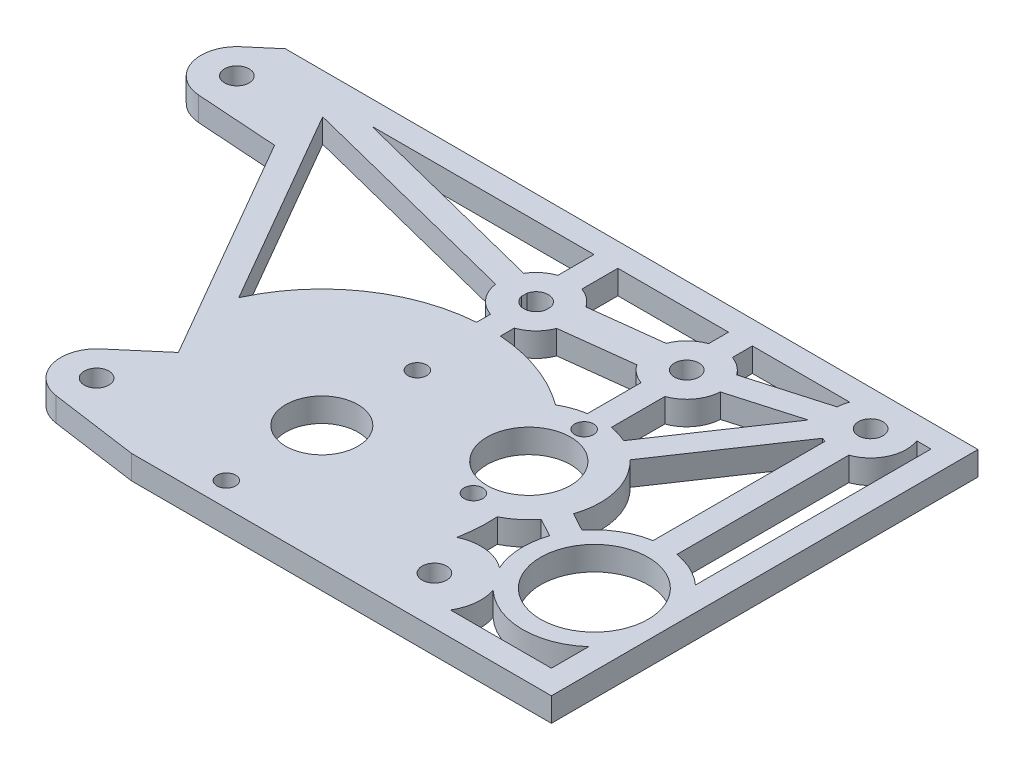
SolidWorks part; units mm, degrees
ref_plane "Front Plane" through (0, 0, 0) normal (0, 0, 1) x (1, 0, 0)
ref_plane "Top Plane" through (0, 0, 0) normal (0, 1, 0) x (1, 0, 0)
ref_plane "Right Plane" through (0, 0, 0) normal (1, 0, 0) x (0, 0, -1)
sketch "Sketch1" plane through (0, 0, 0) normal (0, 1, 0) x (1, 0, 0)
  line L0 (-155.0877, 84.2963) -> (-89.4632, -29.3687)
  line L1 (-89.4632, -29.3687) -> (152.4261, -29.3687)
  line L2 (152.4261, -29.3687) -> (218.0506, 84.2963)
  line L3 (218.0506, 84.2963) -> (-155.0877, 84.2963)
  line L4 (-5.496, 21.6549) -> (-41.275, 2.3813) construction
  line L5 (-5.496, 21.6549) -> (32.4838, 1.1113) construction
  line L6 (61.7749, 67.4068) -> (117.3646, 77.9462) construction
  line L7 (117.3646, 77.9462) -> (98.6972, 24.5341) construction
  line L8 (98.6972, 24.5341) -> (107.7129, -23.0187) construction
  line L9 (61.7749, 67.4068) -> (98.6972, 24.5341) construction
  line L10 (45.9981, 77.1526) -> (118.9398, 90.9819)
  line L11 (45.9981, 77.1526) -> (58.5464, 30.5539)
  line L12 (-140.423, 84.2963) -> (-74.7985, -29.3687) construction
  line L13 (-125.7583, 84.2963) -> (-60.1338, -29.3687) construction
  line L14 (123.0967, -29.3687) -> (188.7212, 84.2963) construction
  line L15 (137.7614, -29.3687) -> (203.3859, 84.2963) construction
  circle A0 centre (-41.275, 2.3813) radius 9.6012
  circle A1 centre (-41.275, 27.7812) radius 2.4892
  circle A2 centre (-41.275, -23.0187) radius 2.4892
  circle A3 centre (-41.275, 2.3813) radius 32.2072
  circle A4 centre (-5.496, 21.6549) radius 11.1252
  circle A5 centre (32.4838, 1.1113) radius 14.3002
  circle A6 centre (-5.496, 21.6549) radius 31.75
  circle A7 centre (61.7749, 67.4068) radius 2.413
  circle A8 centre (117.3646, 77.9462) radius 2.413
  circle A9 centre (107.7129, -23.0187) radius 2.413
  circle A10 centre (32.4838, 1.1113) radius 29.4316
  circle A11 centre (98.6972, 24.5341) radius 40.3225
  circle A12 centre (-133.0907, 71.5963) radius 3.2639
  circle A13 centre (-82.1308, -16.6687) radius 3.2639
  circle A14 centre (196.0536, 71.5963) radius 3.2639
  circle A15 centre (145.0937, -16.6687) radius 3.2639
  point P24 (126.7629, -23.0187)
  dimension "D2" = 56.58
  dimension "D3" = 48.4
  dimension "D4" = 56.5803
  dimension "D5" = 6.35
  dimension "D9" = 56.5803
  dimension "D11" = 12.7
  dimension "D13" = 120
  dimension "D10" = 6.35
  dimension "D12" = 120
  dimension "D14" = 12.7
  dimension "D16" = 113.665
  dimension "D18" = 12.7
  dimension "D19" = 12.7
  dimension "D21" = 12.7
  dimension "D22" = 40.64
  dimension "D23" = 22.2504
  dimension "D24" = 4.9784
  dimension "D25" = 6.5278
  dimension "D26" = 6.5278
  dimension "D27" = 6.5278
  dimension "D28" = 6.5278
  dimension "D29" = 4.9784
  dimension "D30" = 19.2024
  dimension "D31" = 28.6004
  dimension "D32" = 80.645
  dimension "D7" = 19.05
  dimension "D20" = 12.7
  dimension "D34" = 63.5
  dimension "D36" = 30.48
  dimension "D37" = 50.8
  dimension "D38" = 25.4
  dimension "D6" = 25.4
  dimension "D8" = 6.35
  dimension "D15" = 25.4
  dimension "D17" = 12.7
  dimension "D33" = 66.2133
  dimension "D35" = 43.18
sketch "Sketch2" plane through (0, 0, 0) normal (0, 1, 0) x (1, 0, 0)
  line L0 (-155.0877, 84.2962) -> (-89.4632, -29.3687)
  line L1 (82.469, 84.2963) -> (82.469, -29.3687)
  line L3 (-89.4632, -29.3687) -> (152.4261, -29.3687) construction
  line L4 (82.469, -29.3687) -> (-89.4632, -29.3687)
  line L5 (-155.0877, 84.2962) -> (82.469, 84.2963)
  circle A0 centre (-41.275, 2.3813) radius 9.6012
  circle A1 centre (-41.275, 27.7812) radius 2.4892
  circle A2 centre (-41.275, -23.0187) radius 2.4892
  circle A3 centre (-82.1308, -16.6687) radius 3.2639
  circle A4 centre (-133.0907, 71.5962) radius 3.2639
  circle A5 centre (-5.496, 21.6549) radius 11.1252
  circle A6 centre (32.4838, 1.1113) radius 14.3002
  circle A7 centre (61.7749, 67.4068) radius 2.413
  circle A8 centre (76.119, -23.0187) radius 3.2639
  dimension "D1" = 6.5278
  dimension "D2" = 6.5278
  dimension "D3" = 19.2024
  dimension "D4" = 4.9784
  dimension "D5" = 4.9784
  dimension "D6" = 22.2504
  dimension "D7" = 28.6004
  dimension "D8" = 6.5278
  dimension "D9" = 4.826
  dimension "D10" = 6.35
  dimension "D11" = 6.35
  dimension "D12" = 113.665
  dimension "D13" = 120
extrude "Boss-Extrude1" add sketch "Sketch2" along normal blind 6.35
sketch "Sketch3" plane through (0, 6.35, 0) normal (0, 1, 0) x (1, 0, 0)
  line L0 (-125.7583, 84.2963) -> (-60.1338, -29.3687) construction
  line L1 (-112.2405, 73.5827) -> (-81.7457, 20.7641)
  line L2 (218.0506, 84.2963) -> (-155.0877, 84.2963) construction
  line L3 (32.4838, 1.1113) -> (38.8338, -19.8437) construction
  line L4 (-155.0877, 84.2963) -> (-89.4632, -29.3687) construction
  line L5 (-41.275, 2.3813) -> (-5.496, 21.6549) construction
  line L6 (-139.2773, 78.8385) -> (-132.8884, 84.2963)
  line L7 (-133.7338, 62.093) -> (-112.0938, 60.6286)
  line L8 (-88.3175, -9.4265) -> (-77.1535, 0.1103)
  line L9 (-60.1338, -29.3687) -> (-83.4525, -26.1016)
  line L10 (-112.0938, 60.6286) -> (-77.1535, 0.1103)
  line L11 (-140.423, 84.2963) -> (-74.7985, -29.3687) construction
  line L12 (45.1838, 77.9463) -> (45.1838, 15.3103)
  line L13 (-103.5895, 77.9463) -> (-44.45, 77.9463)
  line L14 (-5.496, 21.6549) -> (32.4838, 1.1113) construction
  line L15 (-5.496, 21.6549) -> (-5.496, 77.9463) construction
  line L16 (45.1838, 77.9463) -> (41.3982, 77.9463)
  line L17 (-41.275, 2.3813) -> (-41.275, 77.9463) construction
  line L18 (-132.8884, 84.2963) -> (51.5338, 84.1007)
  line L19 (-60.1338, -29.3687) -> (82.469, -29.3687)
  line L20 (-44.45, 77.9463) -> (-44.45, 68.3571)
  line L21 (-38.1, 77.9463) -> (-38.1, 68.3571)
  line L22 (-8.671, 40.4385) -> (-8.671, 54.6785)
  line L23 (-2.321, 40.4385) -> (-2.321, 54.6785)
  line L24 (-41.275, 59.3769) -> (-5.496, 63.6588) construction
  line L25 (-5.496, 63.6588) -> (32.4819, 74.5959) construction
  line L26 (11.118, 16.2779) -> (17.4729, 12.8405)
  line L27 (9.5149, 9.9257) -> (14.4518, 7.2552)
  line L28 (-41.275, 59.3769) -> (-114.7598, 77.9462) construction
  line L29 (-33.4386, 64.7914) -> (-14.3888, 67.0712)
  line L30 (29.3088, 65.6495) -> (29.3088, 19.8948)
  line L31 (-112.2405, 73.5827) -> (-50.7047, 58.0328)
  line L32 (-103.5895, 77.9463) -> (-49.4499, 64.2653)
  line L33 (-32.3823, 55.9644) -> (-13.3324, 58.2442)
  line L34 (4.0122, 63.0929) -> (22.158, 68.3187)
  line L35 (35.6588, 65.6495) -> (35.6588, 19.8948)
  line L36 (22.158, 68.3187) -> (2.3777, 39.0016)
  line L37 (-44.45, 60.1792) -> (-44.45, 58.6203)
  line L38 (-44.45, 50.3966) -> (-44.45, 46.7177)
  line L39 (-38.1, 60.1335) -> (-38.1, 58.6203)
  line L40 (-38.1, 50.3966) -> (-38.1, 46.7177)
  line L41 (2.2549, 69.1949) -> (22.9737, 75.1617)
  line L42 (-8.671, 72.639) -> (-8.671, 77.9463)
  line L43 (-2.321, 72.639) -> (-2.321, 77.9463)
  line L44 (-2.321, 77.9463) -> (23.5656, 77.9463)
  line L45 (-5.496, 21.6549) -> (-5.496, -23.0187) construction
  line L46 (28.2845, 66.0456) -> (7.6416, 35.45)
  line L47 (51.5338, 1.1113) -> (51.5338, 84.1007)
  line L48 (51.5338, 1.1113) -> (51.5338, -29.3687)
  line L49 (-38.1, 77.9463) -> (-8.671, 77.9463)
  line L50 (20.5334, -23.0187) -> (45.1838, -23.0187)
  line L51 (45.1838, -13.0878) -> (45.1838, -23.0187)
  line L52 (18.3492, -23.0187) -> (20.5334, -23.0187)
  line L53 (82.469, 84.2963) -> (-155.0877, 84.2962) construction
  line L54 (-89.4632, -29.3687) -> (82.469, -29.3687) construction
  arc A0 (-139.2773, 78.8385) -> (-133.7338, 62.093) centre (-133.0907, 71.5962) ccw
  arc A1 (-88.3175, -9.4265) -> (-83.4525, -26.1016) centre (-82.1308, -16.6687) ccw
  circle A2 centre (32.4819, 74.5959) radius 3.2639
  arc A3 (15.1316, -6.7502) -> (2.4799, -5.4492) centre (7.7188, -16.6687) ccw
  arc A4 (-14.947, 38.1952) -> (-81.7457, 20.7641) centre (-41.275, 2.3813) ccw
  arc A5 (14.4518, 7.2552) -> (15.4173, -7.3526) centre (32.4838, 1.1113) ccw
  arc A6 (45.1838, 15.3103) -> (42.9791, 17.0094) centre (32.4838, 1.1113) ccw
  arc A7 (45.1838, 15.3103) -> (37.1708, 19.5757) centre (32.4838, 1.1113) ccw
  arc A8 (-50.7047, 58.0328) -> (-44.45, 50.3966) centre (-41.275, 59.3769) ccw
  arc A9 (-13.3324, 58.2442) -> (-8.671, 54.6785) centre (-5.496, 63.6588) ccw
  circle A10 centre (-41.275, 59.3769) radius 3.2639
  circle A11 centre (-5.496, 63.6588) radius 3.2639
  circle A12 centre (7.7188, -16.6687) radius 3.2639
  arc A13 (-38.1, 50.3966) -> (-32.3823, 55.9644) centre (-41.275, 59.3769) ccw
  arc A14 (-44.45, 68.3571) -> (-49.4499, 64.2653) centre (-41.275, 59.3769) ccw
  arc A15 (-33.4386, 64.7914) -> (-38.1, 68.3571) centre (-41.275, 59.3769) ccw
  arc A16 (2.2549, 69.1949) -> (-2.321, 72.639) centre (-5.496, 63.6588) ccw
  arc A17 (35.6588, 65.6163) -> (41.3982, 77.9463) centre (32.4819, 74.5959) ccw
  arc A18 (28.2845, 66.0456) -> (29.3088, 65.6149) centre (32.4819, 74.5959) ccw
  arc A19 (-8.671, 40.4385) -> (-14.947, 38.1952) centre (-5.496, 21.6549) ccw
  arc A20 (12.536, 15.5109) -> (7.6416, 35.45) centre (-5.496, 21.6549) ccw
  arc A21 (3.1164, 4.6629) -> (9.5149, 9.9257) centre (-5.496, 21.6549) ccw
  circle A22 centre (-5.496, 36.3869) radius 2.4892
  arc A23 (14.4518, 7.2552) -> (15.4173, -7.3526) centre (32.4838, 1.1113) ccw
  arc A24 (18.3492, -23.0187) -> (19.4868, -12.8164) centre (7.7188, -16.6687) ccw
  arc A25 (37.1708, 19.5757) -> (35.6588, 19.8948) centre (32.4838, 1.1113) ccw
  arc A26 (23.5656, 77.9463) -> (22.9737, 75.1617) centre (32.4819, 74.5959) ccw
  arc A27 (-2.321, 54.6785) -> (4.0122, 63.0929) centre (-5.496, 63.6588) ccw
  circle A28 centre (-5.496, 6.9229) radius 2.4892
  arc A29 (-8.671, 72.639) -> (-14.3888, 67.0712) centre (-5.496, 63.6588) ccw
  arc A30 (22.8645, -15.3317) -> (45.1838, -13.0878) centre (32.4838, 1.1113) ccw
  arc A31 (2.4799, -5.4492) -> (3.1164, 4.6629) centre (-41.275, 2.3813) ccw
  arc A32 (29.3088, 19.8948) -> (17.4729, 12.8405) centre (32.4838, 1.1113) ccw
  arc A33 (2.3777, 39.0016) -> (-2.321, 40.4385) centre (-5.496, 21.6549) ccw
  arc A34 (22.8645, -15.3317) -> (38.0085, -17.1201) centre (32.4838, 1.1113) ccw
  arc A35 (19.4868, -12.8164) -> (22.8645, -15.3317) centre (32.4838, 1.1113) ccw
  point P14 (-5.496, 36.3869)
  point P16 (-147.7554, 71.5962)
  point P17 (-142.6157, 62.694)
  point P20 (-96.7955, -16.6687)
  point P66 (-5.496, 6.9229)
  point P67 (-41.275, 59.3769)
  point P68 (-5.496, 58.3863)
  point P125 (-41.275, -23.0187)
  dimension "D2" = 19.05
  dimension "D3" = 19.05
  dimension "D4" = 6.35
  dimension "D6" = 6.35
  dimension "D8" = 4.9784
  dimension "D9" = 38.1
  dimension "D10" = 38.1
  dimension "D13" = 6.35
  dimension "D14" = 19.05
  dimension "D15" = 8.89
  dimension "D19" = 6.5278
  dimension "D20" = 6.5278
  dimension "D21" = 6.5278
  dimension "D22" = 4.9784
  dimension "D26" = 24.765
  dimension "D27" = 6.5278
  dimension "D25" = 12.7
  dimension "D28" = 24.765
  dimension "D29" = 9.525
  dimension "D30" = 6.35
  dimension "D7" = 19.05
  dimension "D11" = 14.2875
  dimension "D31" = 12.7
  dimension "D1" = 6.35
  dimension "D5" = 6.35
  dimension "D12" = 6.35
  dimension "D16" = 6.35
  dimension "D17" = 6.35
  dimension "D18" = 6.35
  dimension "D23" = 14.732
  dimension "D24" = 14.732
  dimension "D35" = 100.505
  dimension "D36" = 123.871
  dimension "D37" = 40.505
extrude "Cut-Extrude1" cut sketch "Sketch3" against normal through all
